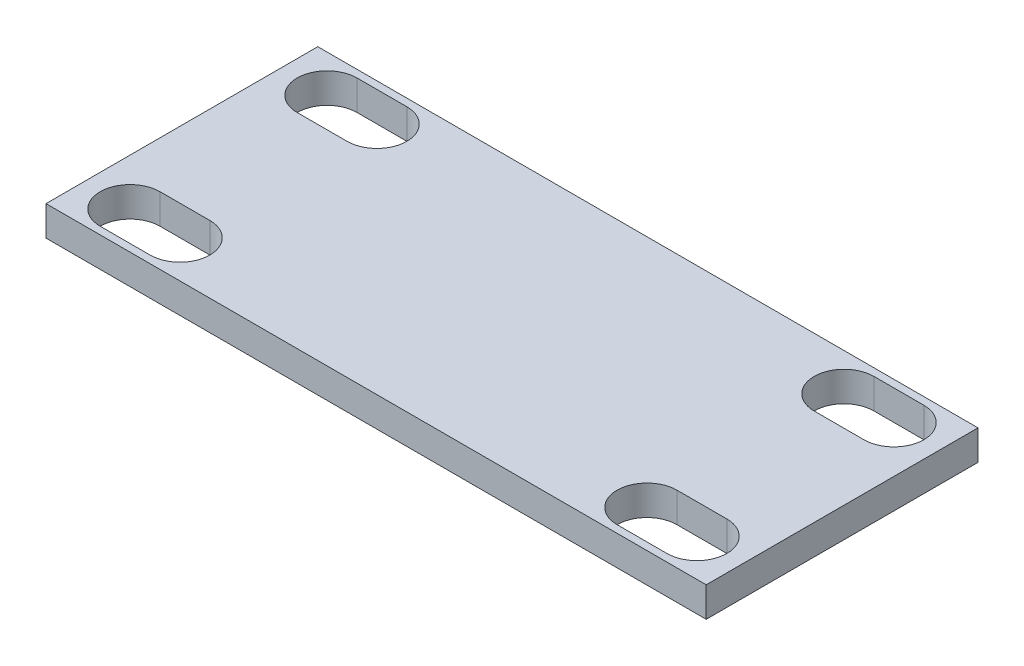
SolidWorks part; units mm, degrees
ref_plane "前视基准面" through (0, 0, 0) normal (0, 0, 1) x (1, 0, 0)
ref_plane "上视基准面" through (0, 0, 0) normal (0, 1, 0) x (1, 0, 0)
ref_plane "右视基准面" through (0, 0, 0) normal (1, 0, 0) x (0, 0, -1)
sketch "草图1" plane through (0, 0, 0) normal (0, 1, 0) x (1, 0, 0)
  line L0 (-28.4129, 9.875) -> (-23.4129, 9.875) construction
  line L1 (-33.095, 13.625) -> (33.095, 13.625)
  line L2 (-33.095, 13.625) -> (-33.095, -13.625)
  line L3 (-33.095, -13.625) -> (33.095, -13.625)
  line L4 (33.095, 13.625) -> (33.095, -13.625)
  line L5 (-33.095, 13.625) -> (33.095, -13.625) construction
  line L6 (-33.095, -13.625) -> (33.095, 13.625) construction
  line L7 (-28.4129, 12.875) -> (-23.4129, 12.875)
  line L8 (-28.4129, 6.875) -> (-23.4129, 6.875)
  line L9 (0, 0) -> (0, 6.1667) construction
  line L10 (0, 0) -> (-7.9433, 0) construction
  line L11 (28.4129, 9.875) -> (23.4129, 9.875) construction
  line L12 (28.4129, 12.875) -> (23.4129, 12.875)
  line L13 (28.4129, 6.875) -> (23.4129, 6.875)
  line L14 (-28.4129, -9.875) -> (-23.4129, -9.875) construction
  line L15 (-28.4129, -12.875) -> (-23.4129, -12.875)
  line L16 (-28.4129, -6.875) -> (-23.4129, -6.875)
  line L17 (28.4129, -9.875) -> (23.4129, -9.875) construction
  line L18 (28.4129, -12.875) -> (23.4129, -12.875)
  line L19 (28.4129, -6.875) -> (23.4129, -6.875)
  arc A0 (-28.4129, 12.875) -> (-28.4129, 6.875) centre (-28.4129, 9.875) ccw
  arc A1 (-23.4129, 6.875) -> (-23.4129, 12.875) centre (-23.4129, 9.875) ccw
  arc A2 (28.4129, 12.875) -> (28.4129, 6.875) centre (28.4129, 9.875) cw
  arc A3 (23.4129, 6.875) -> (23.4129, 12.875) centre (23.4129, 9.875) cw
  arc A4 (-28.4129, -12.875) -> (-28.4129, -6.875) centre (-28.4129, -9.875) cw
  arc A5 (-23.4129, -6.875) -> (-23.4129, -12.875) centre (-23.4129, -9.875) cw
  arc A6 (28.4129, -12.875) -> (28.4129, -6.875) centre (28.4129, -9.875) ccw
  arc A7 (23.4129, -6.875) -> (23.4129, -12.875) centre (23.4129, -9.875) ccw
  point P0 (0, 0)
  point P8 (-25.9129, 9.875)
  point P18 (25.9129, 9.875)
  point P25 (-25.9129, -9.875)
  point P32 (25.9129, -9.875)
  dimension "D3" = 3
  dimension "D5" = 9.875
  dimension "D1" = 66.19
  dimension "D2" = 27.25
  dimension "D4" = 5
extrude "凸台-拉伸1" add sketch "草图1" along normal blind 3
